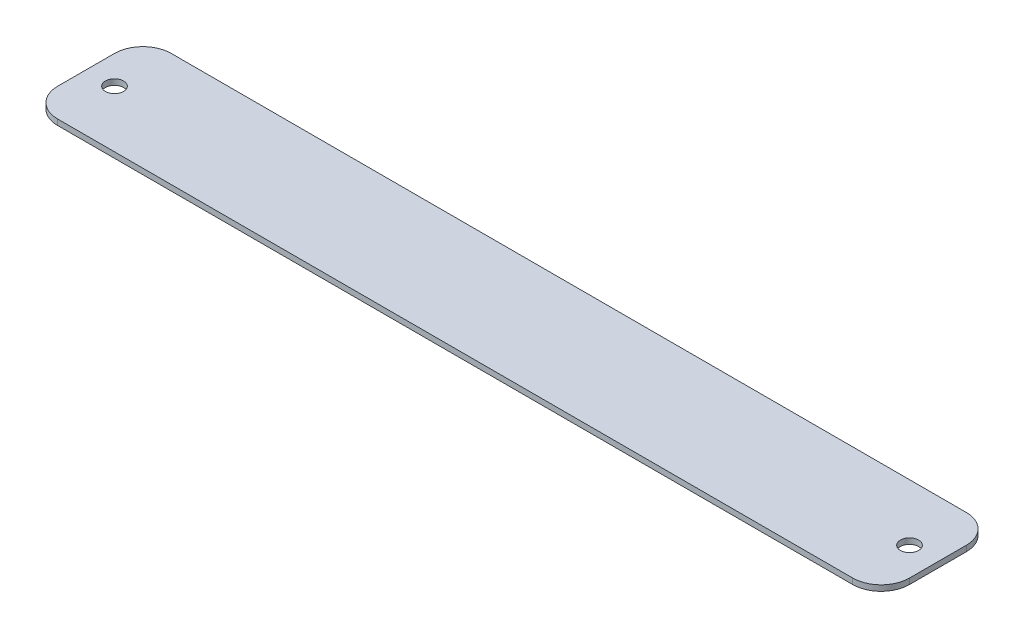
SolidWorks part; units mm, degrees
ref_plane "前视基准面" through (0, 0, 0) normal (0, 0, 1) x (1, 0, 0)
ref_plane "上视基准面" through (0, 0, 0) normal (0, 1, 0) x (1, 0, 0)
ref_plane "右视基准面" through (0, 0, 0) normal (1, 0, 0) x (0, 0, -1)
other "Configuration Table"
sketch "草图1" plane through (0, 0, 0) normal (0, 1, 0) x (1, 0, 0)
  line L0 (-75, 0) -> (75, 0) construction
  line L1 (-75, 10) -> (75, 10)
  line L2 (-75, 10) -> (-75, -10)
  line L3 (-75, -10) -> (75, -10)
  line L4 (75, 10) -> (75, -10)
  line L5 (-75, 10) -> (75, -10) construction
  line L6 (-75, -10) -> (75, 10) construction
  line L7 (0, 0) -> (0, -10) construction
  circle A0 centre (-70, 0) radius 1.6
  circle A1 centre (70, 0) radius 1.6
  point P0 (0, 0)
  dimension "D3" = 3.2
  dimension "D1" = 150
  dimension "D2" = 20
  dimension "D4" = 140
extrude "凸台-拉伸1" add sketch "草图1" along normal blind 1
fillet "圆角1" radius 5 4 edges at (-75, 0.5, 10) (-75, 0.5, -10) (75, 0.5, -10) (75, 0.5, 10)
